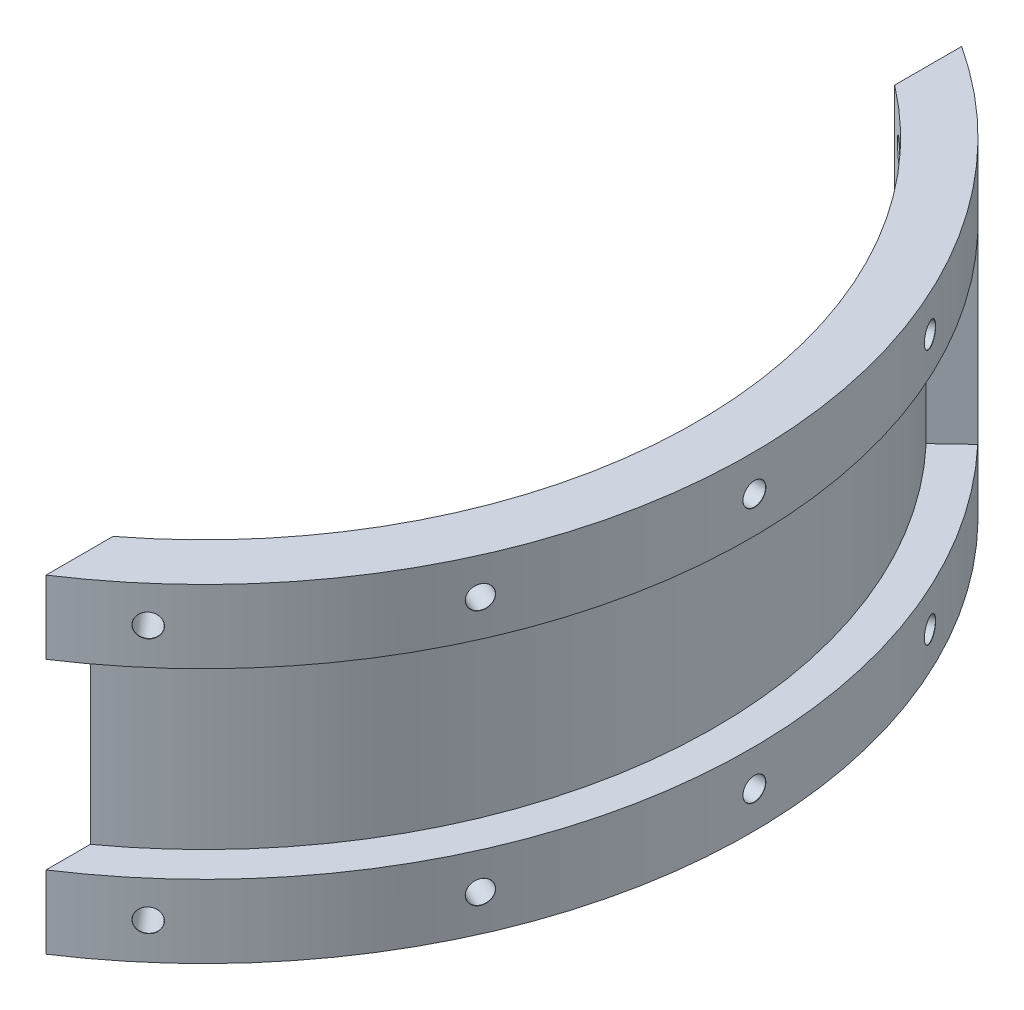
SolidWorks part; units mm, degrees
material "PE High Density"
ref_plane "Front Plane" through (0, 0, 0) normal (0, 0, 1) x (1, 0, 0)
ref_plane "Top Plane" through (0, 0, 0) normal (0, 1, 0) x (1, 0, 0)
ref_plane "Right Plane" through (0, 0, 0) normal (1, 0, 0) x (0, 0, -1)
sketch "Sketch2" plane through (0, 0, 0) normal (0, 1, 0) x (1, 0, 0)
  line L0 (-1000, 0) -> (49000, 0) construction
  line L1 (0, -1000) -> (0, 49000) construction
  line L2 (39.8113, 36.4838) -> (39.8113, 0) construction
  line L3 (32.8573, 50.2036) -> (32.8573, 0) construction
  line L12 (32.8573, 42.8532) -> (32.8573, 50.2036)
  line L14 (32.8573, -50.2036) -> (32.8573, -42.8532)
  arc A0 (54, 0) -> (39.8113, 36.4838) centre (0, 0) ccw construction
  arc A1 (32.8573, -50.2036) -> (32.8573, 50.2036) centre (0, 0) ccw
  arc A2 (0, -60) -> (0, 60) centre (0, 0) ccw construction
  arc A3 (0, -54) -> (0, 54) centre (0, 0) ccw construction
  arc A5 (32.8573, -42.8532) -> (32.8573, 42.8532) centre (0, 0) ccw
  dimension "D1" = 54
  dimension "D2" = 6
  dimension "D3" = 99
extrude "Boss-Extrude1" add sketch "Sketch2" along normal blind 36
sketch "Sketch4" plane through (0, 36, 0) normal (0, 1, 0) x (1, 0, 0)
  line L0 (-1000, 0) -> (49000, 0) construction
  line L1 (0, -1000) -> (0, 49000) construction
  line L6 (40.6307, 38.5375) -> (43.5329, 41.2902)
  line L7 (0, -56) -> (0, -60)
  arc A2 (32.8573, -50.2036) -> (32.8573, 50.2036) centre (0, 0) ccw construction
  arc A4 (32.8573, -50.2036) -> (43.5329, 41.2902) centre (0, 0) ccw construction
  arc A8 (0, -60) -> (43.5329, 41.2902) centre (0, 0) ccw
  arc A9 (0, -56) -> (40.6307, 38.5375) centre (0, 0) ccw
  dimension "D1" = 56
  dimension "D2" = 4
  dimension "D3" = 4
extrude "Cut-Extrude1" cut sketch "Sketch4" against normal blind 10 and the other way blind 10 from offset 18 offset against normal yes
hole_wizard "Tap Drill for M3x0.5 Tap3" positions "3DSketch7" profile "Sketch10" hole size "M3x0.5" standard "ANSI Metric"
sketch3d "3DSketch7"
  line L0 (32.8573, 36, -50.2036) -> (32.8573, 0, -50.2036) construction
  line L1 (32.8573, 36, 50.2036) -> (32.8573, 28, 50.2036) construction
  line L2 (32.8573, 8, 50.2036) -> (32.8573, 0, 50.2036) construction
  point P0 (39.2442, 32, -45.3861)
  point P2 (54.4929, 32, -25.1102)
  point P4 (59.999, 32, -0.3449)
  point P6 (54.778, 32, 24.4821)
  point P8 (39.2442, 32, 45.3861)
  point P10 (39.2442, 4, 45.3861)
  point P12 (54.778, 4, 24.4821)
  point P14 (59.999, 4, -0.3449)
  point P16 (54.4929, 4, -25.1102)
  point P18 (39.2442, 4, -45.3861)
  dimension "D1" = 8
  dimension "D2" = 4
  dimension "D3" = 4
  dimension "D4" = 4
  dimension "D5" = 4
  dimension "D6" = 4
  dimension "D7" = 4
  dimension "D8" = 4
  dimension "D9" = 4
  dimension "D10" = 4
  dimension "D11" = 4
  dimension "D12" = 25.37
  dimension "D13" = 25.37
  dimension "D14" = 25.37
  dimension "D15" = 25.37
  dimension "D16" = 25.37
  dimension "D17" = 25.37
  dimension "D18" = 8
  dimension "D19" = 8
  dimension "D20" = 8
sketch "Sketch10" plane through (39.2442, 32, -45.3861) normal (0, 1, 0) x (-0.7564, 0, -0.6541)
  line L0 (0, 0) -> (0, 10.7511)
  line L1 (0, 10.7511) -> (1.25, 10)
  line L2 (1.25, 10) -> (1.25, 0.025)
  line L3 (1.25, 0.025) -> (1.275, 0)
  line L5 (1.275, 0) -> (0, 0)
  line L6 (-1.25, 0.025) -> (-1.275, 0) construction
  line L10 (0, 10.7511) -> (-1.25, 10) construction
  line L11 (0, -6.35) -> (0, 107.95) construction
  dimension "Hole Dia." = 2.5
  dimension "Hole Depth" = 10
  dimension "Near C'Sink Dia." = 2.55
  dimension "Near C'Sink Angle" = 90
  dimension "Drill Angle" = 118
